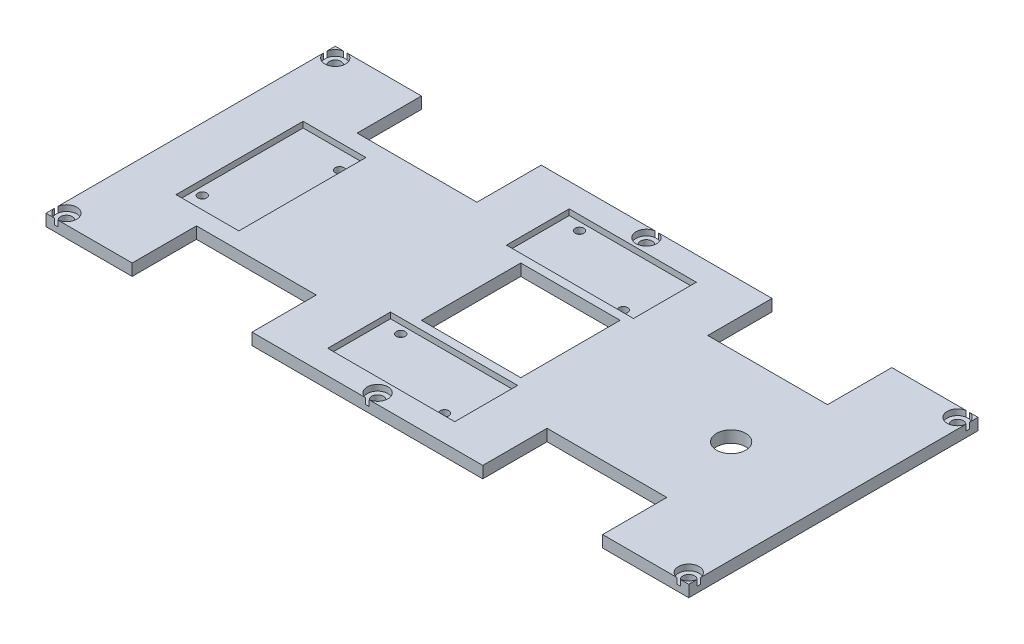
SolidWorks part; units mm, degrees
material "ABS"
ref_plane "前基準面" through (0, 0, 0) normal (0, 0, 1) x (1, 0, 0)
ref_plane "上基準面" through (0, 0, 0) normal (0, 1, 0) x (1, 0, 0)
ref_plane "右基準面" through (0, 0, 0) normal (1, 0, 0) x (0, 0, -1)
sketch "草圖1" plane through (0, 0, 0) normal (0, 1, 0) x (1, 0, 0)
  line L6 (0, 0) -> (0, 50.47) construction
  line L9 (0, 0) -> (-33.4572, 0) construction
  line L25 (-39.5, 49.5) -> (39.5, 49.5)
  line L26 (-39.5, -49.5) -> (39.5, -49.5)
  line L33 (-110, 49.5) -> (-110, -49.5)
  line L36 (-80.5, 49.5) -> (-110, 49.5)
  line L37 (-80.5, 27.5) -> (-80.5, 49.5)
  line L40 (-39.5, 49.5) -> (-39.5, 27.5)
  line L41 (-39.5, 27.5) -> (-80.5, 27.5)
  line L42 (-39.5, -27.5) -> (-80.5, -27.5)
  line L43 (-39.5, -49.5) -> (-39.5, -27.5)
  line L46 (-80.5, -27.5) -> (-80.5, -49.5)
  line L47 (-80.5, -49.5) -> (-110, -49.5)
  line L55 (80.5, -49.5) -> (110, -49.5)
  line L56 (80.5, -27.5) -> (80.5, -49.5)
  line L59 (39.5, -49.5) -> (39.5, -27.5)
  line L60 (39.5, -27.5) -> (80.5, -27.5)
  line L61 (39.5, 27.5) -> (80.5, 27.5)
  line L62 (39.5, 49.5) -> (39.5, 27.5)
  line L65 (80.5, 27.5) -> (80.5, 49.5)
  line L66 (80.5, 49.5) -> (110, 49.5)
  line L69 (110, 49.5) -> (110, -49.5)
  point P0 (0, 0)
  point P7 (110, 0)
  point P55 (-110, 0)
  dimension "D1" = 99
  dimension "D2" = 29.5
  dimension "D3" = 22
  dimension "D4" = 41
  dimension "D5" = 110
extrude "填料-伸長1" add sketch "草圖1" along normal blind 4
sketch "草圖11" plane through (0, 0, 0) normal (0, 1, 0) x (1, 0, 0)
  line L0 (0, -999.75) -> (0, 49000.25) construction
  line L1 (-1000.25, 0) -> (-60.5986, 0) construction
  line L4 (-14, 17) -> (20, 17)
  line L5 (-14, 17) -> (-14, -17)
  line L6 (-14, -17) -> (20, -17)
  line L7 (-110, 49.5) -> (-110, -49.5) construction
  line L8 (-80.5, 49.5) -> (-110, 49.5) construction
  line L9 (20, 17) -> (20, -17)
  line L25 (-60.5986, 0) -> (48999.75, 0) construction
  circle A0 centre (-106.5, 46) radius 2
  circle A1 centre (0, 46) radius 2
  circle A2 centre (106.5, 46) radius 2
  circle A3 centre (0, -46) radius 2
  circle A4 centre (-106.5, -46) radius 2
  circle A5 centre (106.5, -46) radius 2
  circle A6 centre (75, 0) radius 5
  dimension "D1" = 4
  dimension "D9" = 10
  dimension "D2" = 3.5
  dimension "D3" = 3.5
  dimension "D4" = 3.5
  dimension "D5" = 34
  dimension "D6" = 34
  dimension "D7" = 14
  dimension "D8" = 75
extrude "除料-伸長8" cut sketch "草圖11" along normal through all
sketch "草圖12" plane through (0, 4, 0) normal (0, 1, 0) x (1, 0, 0)
  line L0 (0, 0) -> (54.8152, 0) construction
  line L1 (0, 0) -> (0, 72.3045) construction
  circle A77 centre (-106.5, 46) radius 3.55
  circle A78 centre (0, 46) radius 3.55
  circle A79 centre (0, -46) radius 3.55
  circle A80 centre (-106.5, -46) radius 3.55
  circle A81 centre (106.5, -46) radius 3.55
  circle A82 centre (106.5, 46) radius 3.55
  circle A83 centre (0, 46) radius 2 construction
  circle A84 centre (-106.5, 46) radius 2 construction
  dimension "D1" = 7.1
extrude "除料-伸長9" cut sketch "草圖12" against normal blind 2
sketch "草圖13" plane through (0, 4, 0) normal (0, 1, 0) x (1, 0, 0)
  line L0 (0, 0) -> (-118.8994, 0) construction
  line L1 (-93.25, -21.75) -> (-71.75, -21.75)
  line L2 (-93.25, -21.75) -> (-93.25, 21.75)
  line L3 (-93.25, 21.75) -> (-71.75, 21.75)
  line L4 (-71.75, -21.75) -> (-71.75, 21.75)
  line L5 (-93.25, -21.75) -> (-71.75, 21.75) construction
  line L6 (-93.25, 21.75) -> (-71.75, -21.75) construction
  line L7 (0, 0) -> (0, 101.2029) construction
  line L8 (-21.75, -41.3381) -> (21.75, -41.3381)
  line L9 (-21.75, 19.8381) -> (21.75, 19.8381)
  line L10 (-21.75, 19.8381) -> (-21.75, 41.3381)
  line L11 (-21.75, 41.3381) -> (21.75, 41.3381)
  line L12 (21.75, 19.8381) -> (21.75, 41.3381)
  line L13 (-21.75, 19.8381) -> (21.75, 41.3381) construction
  line L14 (-21.75, 41.3381) -> (21.75, 19.8381) construction
  line L15 (21.75, -19.8381) -> (21.75, -41.3381)
  line L16 (-21.75, -19.8381) -> (21.75, -19.8381)
  line L17 (-21.75, -19.8381) -> (-21.75, -41.3381)
  point P0 (-82.5, 0)
  point P5 (0, 30.5881)
  dimension "D1" = 21.5
  dimension "D2" = 43.5
  dimension "D3" = 82.5
  dimension "D4" = 21.5
  dimension "D5" = 43.5
extrude "除料-伸長10" cut sketch "草圖13" against normal blind 2
sketch "草圖14" plane through (0, 2, 0) normal (0, 1, 0) x (1, 0, 0)
  line L0 (-82.5, 21.75) -> (-82.5, -21.75) construction
  line L1 (-71.75, 21.75) -> (-93.25, 21.75) construction
  line L2 (-93.25, -21.75) -> (-71.75, -21.75) construction
  line L3 (-93.25, 0) -> (-71.75, 0) construction
  line L4 (-93.25, 21.75) -> (-93.25, -21.75) construction
  line L5 (-71.75, -21.75) -> (-71.75, 21.75) construction
  line L6 (-21.75, 30.5881) -> (21.75, 30.5881) construction
  line L7 (-21.75, 41.3381) -> (-21.75, 19.8381) construction
  line L8 (21.75, 19.8381) -> (21.75, 41.3381) construction
  line L9 (0, 41.3381) -> (0, 19.8381) construction
  line L10 (21.75, 41.3381) -> (-21.75, 41.3381) construction
  line L11 (-21.75, 19.8381) -> (21.75, 19.8381) construction
  line L12 (0, 0) -> (-134.4303, 0) construction
  circle A0 centre (-74.5, 15.5) radius 1.5
  circle A1 centre (-90.5, -15.5) radius 1.5
  circle A4 centre (-15.5, -22.5881) radius 1.5
  circle A5 centre (15.5, -38.5881) radius 1.5
  circle A6 centre (15.5, 22.5881) radius 1.5
  circle A7 centre (-15.5, 38.5881) radius 1.5
  dimension "D5" = 3
  dimension "D6" = 8
  dimension "D8" = 3
  dimension "D1" = 15.5
  dimension "D2" = 8
  dimension "D3" = 8
  dimension "D4" = 15.5
  dimension "D7" = 15.5
  dimension "D9" = 15.5
  dimension "D10" = 8
extrude "除料-伸長11" cut sketch "草圖14" against normal through all
